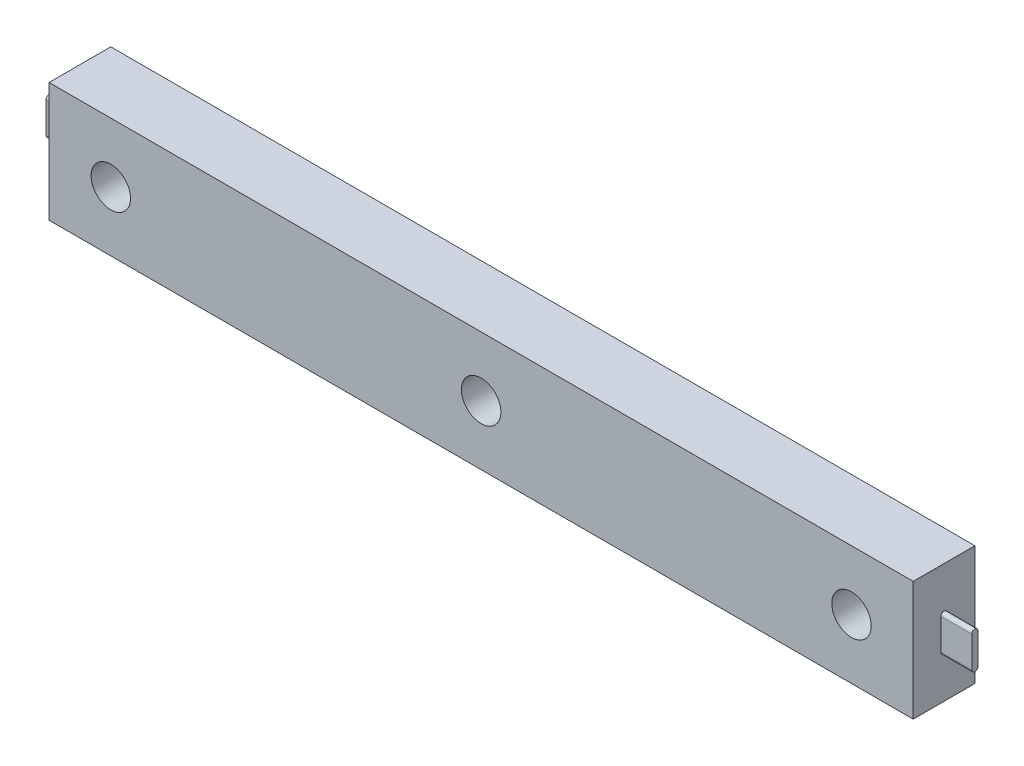
SolidWorks part; units mm, degrees
ref_plane "Front Plane" through (0, 0, 0) normal (0, 0, 1) x (1, 0, 0)
ref_plane "Top Plane" through (0, 0, 0) normal (0, 1, 0) x (1, 0, 0)
ref_plane "Right Plane" through (0, 0, 0) normal (1, 0, 0) x (0, 0, -1)
sketch "Sketch1" plane through (0, 0, 0) normal (0, 0, 1) x (1, 0, 0)
  line L1 (-88.9, -12.2777) -> (88.9, -12.2777)
  line L2 (-88.9, -12.2777) -> (-88.9, 12.2777)
  line L3 (-88.9, 12.2777) -> (88.9, 12.2777)
  line L4 (88.9, -12.2777) -> (88.9, 12.2777)
  line L5 (-88.9, -12.2777) -> (88.9, 12.2777) construction
  line L6 (-88.9, 12.2777) -> (88.9, -12.2777) construction
  circle A0 centre (0, 0) radius 4.064
  circle A1 centre (-76.2, 0) radius 4.064
  circle A2 centre (76.2, 0) radius 4.064
  point P0 (0, 0)
  dimension "D1" = 8.128
  dimension "D2" = 8.128
  dimension "D3" = 8.128
  dimension "D4" = 76.2
  dimension "D5" = 76.2
  dimension "D6" = 177.8
extrude "Boss-Extrude1" add sketch "Sketch1" along normal blind 12.7
sketch "Sketch2" plane through (-88.9, 0, 0) normal (-1, 0, 0) x (0, 0, 1)
  line L3 (5.715, -3.175) -> (5.715, 3.175)
  line L4 (6.985, 3.175) -> (6.985, -3.175)
  arc A1 (6.985, 3.175) -> (5.715, 3.175) centre (6.35, 3.175) ccw
  arc A2 (5.715, -3.175) -> (6.985, -3.175) centre (6.35, -3.175) ccw
  dimension "D2" = 1.27
  dimension "D3" = 1.27
extrude "Boss-Extrude2" add sketch "Sketch2" along normal blind 6.35
sketch "Sketch3" plane through (88.9, 0, 0) normal (1, 0, 0) x (0, 0, -1)
  line L0 (-5.715, 3.175) -> (-5.715, -3.175)
  line L1 (-6.985, -3.175) -> (-6.985, 3.175)
  arc A0 (-5.715, 3.175) -> (-6.985, 3.175) centre (-6.35, 3.175) ccw
  arc A1 (-6.985, -3.175) -> (-5.715, -3.175) centre (-6.35, -3.175) ccw
  dimension "D1" = 1.27
  dimension "D2" = 1.27
extrude "Boss-Extrude3" add sketch "Sketch3" along normal blind 6.35
